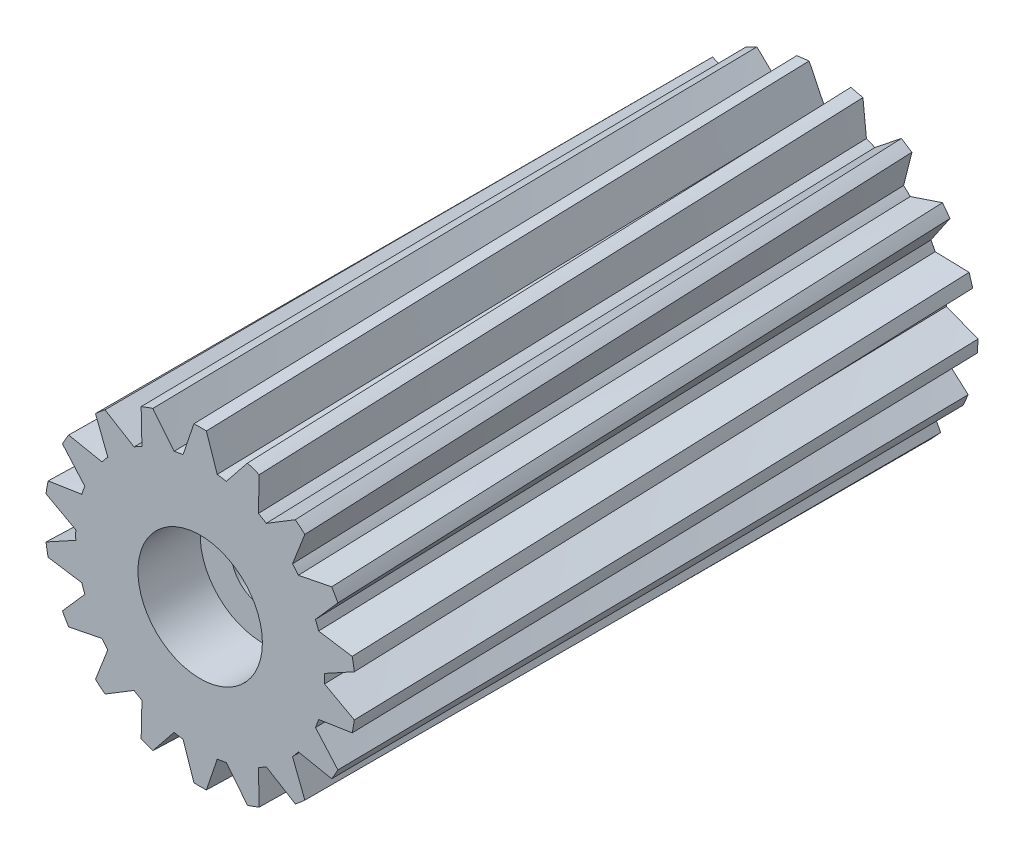
SolidWorks part; units mm, degrees
ref_plane "Front Plane" through (0, 0, 0) normal (0, 0, 1) x (1, 0, 0)
ref_plane "Top Plane" through (0, 0, 0) normal (0, 1, 0) x (1, 0, 0)
ref_plane "Right Plane" through (0, 0, 0) normal (1, 0, 0) x (0, 0, -1)
sketch "Sketch1" plane through (0, 0, 0) normal (0, 0, 1) x (1, 0, 0)
  line L0 (0, 0) -> (0, 87.586) construction
  circle A0 centre (0, 35) radius 20
  circle A1 centre (0, 0) radius 10 construction
  arc A2 (-4.1089, 9.1168) -> (-5.841, 8.1168) centre (0, 0) ccw construction
  arc A3 (4.5724, 14.2861) -> (-0.876, 14.9744) centre (0, 0) ccw construction
  point P8 (0, 25.4177)
  point P10 (0, 35.9578)
  dimension "D2" = 40
extrude "Boss-Extrude1" add sketch "Sketch1" against normal blind 100 contours A0
sketch "Sketch2" plane through (0, 0, 0) normal (0, 0, 1) x (1, 0, 0)
  circle A0 centre (0, 35) radius 10
  dimension "D1" = 20
extrude "Cut-Extrude1" cut sketch "Sketch2" against normal blind 10
sketch "Sketch4" plane through (0, 0, 0) normal (0, 0, 1) x (1, 0, 0)
  circle A0 centre (0, 35) radius 20 construction
  circle A1 centre (0, 35) radius 20
curve "Helix/Spiral1" pitch 5000 height 100 turns 0.02
sketch "Sketch5" plane through (0, 0, -100) normal (0, 0, -1) x (-1, 0, 0)
  circle A0 centre (0, 35) radius 10
  circle A1 centre (0, 35) radius 10 construction
sketch "Sketch6" plane through (0, 0, -10) normal (0, 0, 1) x (1, 0, 0)
  circle A0 centre (0, 35) radius 5
  dimension "D1" = 10
extrude "Cut-Extrude3" cut sketch "Sketch6" against normal through all
sketch "Sketch7" plane through (0, 0, 0) normal (0, 0, 1) x (1, 0, 0)
  line L0 (0, 15) -> (0, 8.1817) construction
  line L1 (1, 10.02) -> (2.75, 15.19)
  line L2 (-1, 10.02) -> (-2.75, 15.19)
  circle A0 centre (0, 35) radius 20 construction
  arc A1 (-2.75, 15.19) -> (2.75, 15.19) centre (0, 35) ccw
  arc A2 (-1, 10.02) -> (1, 10.02) centre (0, 35) ccw
  arc A3 (1, 9.9499) -> (-1, 9.9499) centre (0, 0) ccw construction
  dimension "D1" = 1
  dimension "D2" = 2.75
sweep "Sweep1" add profiles "Sketch7" path "Helix/Spiral1"
pattern_circular "CirPattern1" count 18 over 360 about axis through (0, 35, -10) along (0, 0, 1) of "Sweep1"
